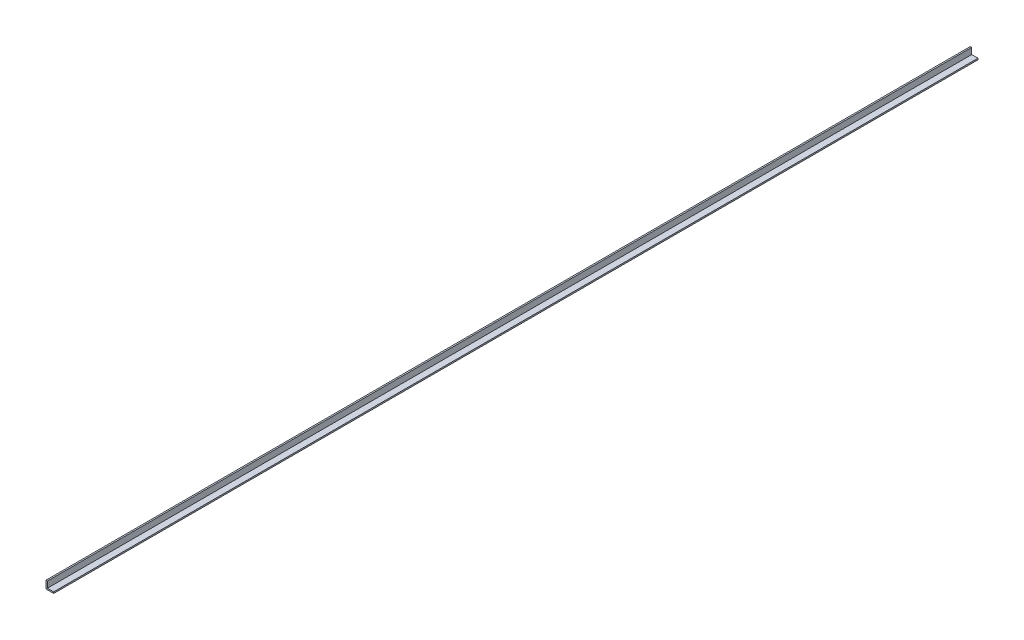
SolidWorks part; units mm, degrees
material "ASTM A36 Acero"
ref_plane "Alzado" through (0, 0, 0) normal (0, 0, 1) x (1, 0, 0)
ref_plane "Planta" through (0, 0, 0) normal (0, 1, 0) x (1, 0, 0)
ref_plane "Vista lateral" through (0, 0, 0) normal (1, 0, 0) x (0, 0, -1)
sketch "Croquis1" plane through (0, 0, 0) normal (0, 0, 1) x (1, 0, 0)
  line L0 (0, 50.8) -> (0, 0)
  line L1 (0, 0) -> (50.8, 0)
  line L2 (50.8, 0) -> (50.8, 9.53)
  line L3 (50.8, 9.53) -> (9.53, 9.53)
  line L4 (9.53, 9.53) -> (9.53, 50.8)
  line L5 (9.53, 50.8) -> (0, 50.8)
  dimension "D1" = 9.53
  dimension "D2" = 50.8
extrude "Saliente-Extruir1" add sketch "Croquis1" against normal blind 6100
